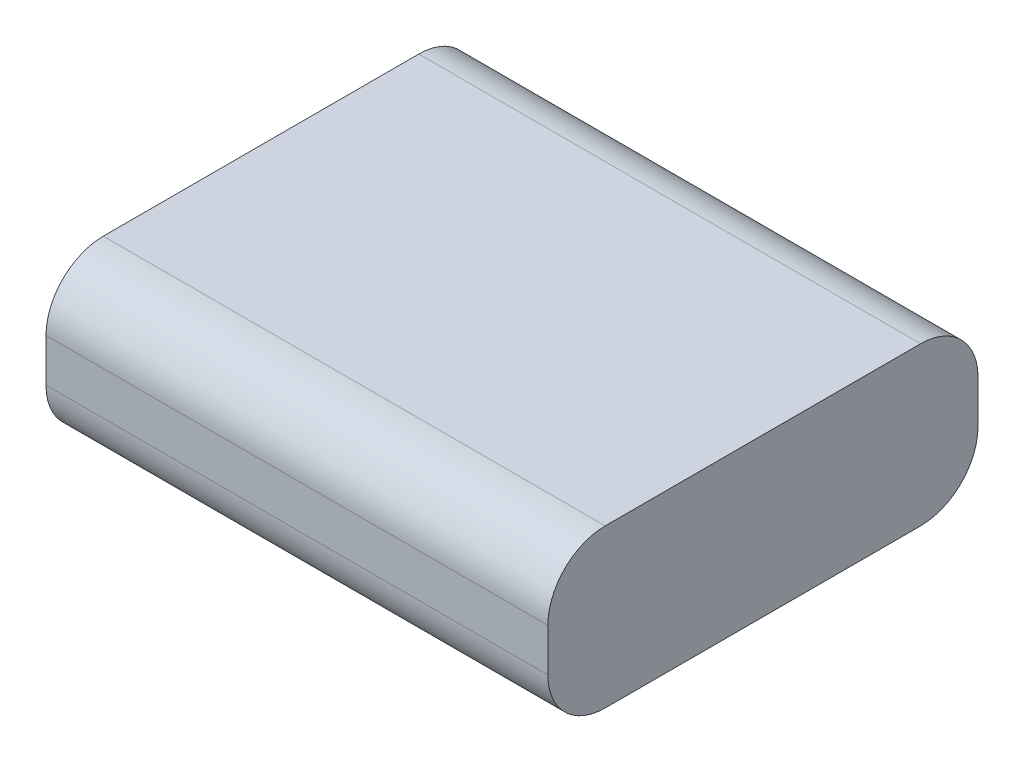
SolidWorks part; units mm, degrees
ref_plane "前视基准面" through (0, 0, 0) normal (0, 0, 1) x (1, 0, 0)
ref_plane "上视基准面" through (0, 0, 0) normal (0, 1, 0) x (1, 0, 0)
ref_plane "右视基准面" through (0, 0, 0) normal (1, 0, 0) x (0, 0, -1)
other "Configuration Table"
sketch "草图1" plane through (0, 0, 0) normal (0, 1, 0) x (1, 0, 0)
  line L1 (-35, 30) -> (35, 30)
  line L2 (-35, 30) -> (-35, -30)
  line L3 (-35, -30) -> (35, -30)
  line L4 (35, 30) -> (35, -30)
  line L5 (-35, 30) -> (35, -30) construction
  line L6 (-35, -30) -> (35, 30) construction
  point P0 (0, 0)
  dimension "D1" = 60
  dimension "D2" = 70
extrude "凸台-拉伸1" add sketch "草图1" along normal blind 22
fillet "圆角1" radius 8 4 edges at (0, 0, 30) (0, 0, -30) (0, 22, 30) (0, 22, -30)
